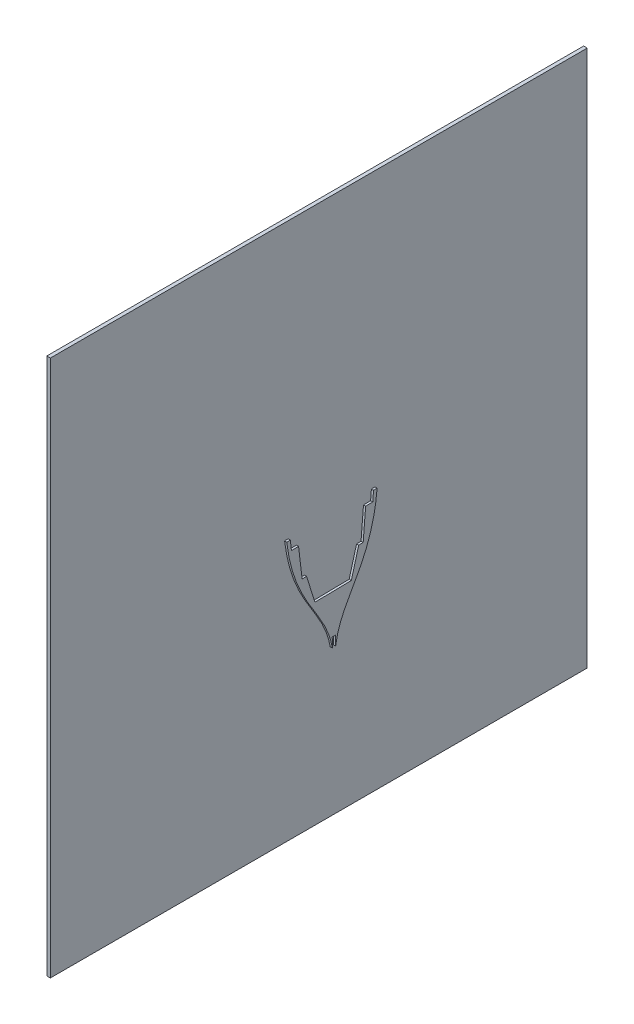
SolidWorks part; units mm, degrees
ref_plane "Plan de face" through (0, 0, 0) normal (0, 0, 1) x (1, 0, 0)
ref_plane "Plan de dessus" through (0, 0, 0) normal (0, 1, 0) x (1, 0, 0)
ref_plane "Plan de droite" through (0, 0, 0) normal (1, 0, 0) x (0, 0, -1)
sketch "Esquisse1" plane through (0, 0, 0) normal (0, 0, 1) x (1, 0, 0)
  point P0 (-20, 0)
  dimension "D1" = 20
sketch3d "Esquisse3D1"
  line L1 (-20, 1121.2893, 777.275) -> (-20, 1121.2893, -722.725)
  line L2 (-20, 1121.2893, 777.275) -> (-20, -378.7107, 777.275)
  line L3 (-20, -378.7107, 777.275) -> (-20, -378.7107, -722.725)
  line L4 (-20, 1121.2893, -722.725) -> (-20, -378.7107, -722.725)
  dimension "D1" = 1500
  dimension "D2" = 1500
extrude "Boss.-Extru.2" add sketch "Esquisse3D1" along direction (1, 0, 0) on the side of the normal blind 10 contours L2 L1 L4 L3
sketch "Esquisse4" plane through (-10, 0, 0) normal (1, 0, 0) x (0, 0, -1)
  line L0 (0, 0) -> (-7.701, 425.1082) construction
  line L1 (169.3944, 339.9131) -> (-188.5193, 333.4294) construction
  line L2 (-187.2006, 249.23) -> (169.0622, 255.6839) construction
  line L3 (-144.268, 175.2448) -> (126.4811, 180.1495) construction
sketch "Esquisse5" plane through (0, 0, 0) normal (1, 0, 0) x (0, 0, -1)
  line L0 (-7.701, 425.1082) -> (0, 0) construction
  line L2 (0, 0) -> (3.7943, 58.3884) construction
  line L3 (3.7943, 58.3884) -> (5.4733, 142.9265) construction
  line L4 (5.4733, 142.9265) -> (102.9324, 168.1895) construction
  line L5 (102.9324, 168.1895) -> (119.6506, 366.1761) construction
  line L8 (119.6506, 366.1761) -> (109.6506, 365.9949)
  line L9 (109.6506, 365.9949) -> (107.5151, 338.7922)
  line L10 (169.3944, 339.9131) -> (-188.5193, 333.4294) construction
  line L11 (107.5151, 338.7922) -> (87.5835, 338.4311)
  line L12 (87.5835, 338.4311) -> (80.739, 254.0839)
  line L13 (-187.2006, 249.23) -> (169.0622, 255.6839) construction
  line L14 (80.739, 254.0839) -> (68.2687, 253.858)
  line L15 (68.2687, 253.858) -> (47.6553, 178.7215)
  line L16 (-144.268, 175.2448) -> (126.4811, 180.1495) construction
  line L17 (47.6553, 178.7215) -> (-54.0971, 176.8782)
  line L18 (0, 0) -> (-5.9065, 58.2127) construction
  line L19 (-5.9065, 58.2127) -> (-10.6464, 142.6345) construction
  line L20 (-10.6464, 142.6345) -> (-108.9565, 164.351) construction
  line L21 (-108.9565, 164.351) -> (-132.8346, 361.6022) construction
  line L22 (-77.4184, 251.2188) -> (-54.0971, 176.8782)
  line L23 (-89.8887, 250.9929) -> (-77.4184, 251.2188)
  line L24 (-99.7836, 335.0369) -> (-89.8887, 250.9929)
  line L25 (-119.7152, 334.6758) -> (-99.7836, 335.0369)
  line L26 (-122.8346, 361.7834) -> (-119.7152, 334.6758)
  line L27 (-132.8346, 361.6022) -> (-122.8346, 361.7834)
  spline S0 degree 4 poles (0, 0) (3.7943, 58.3884) (5.4733, 142.9265) (102.9324, 168.1895) (119.6506, 366.1761) knots 0 0 0 0 0 1 1 1 1 1
  spline S1 degree 4 poles (0, 0) (-5.9065, 58.2127) (-10.6464, 142.6345) (-108.9565, 164.351) (-132.8346, 361.6022) knots 0 0 0 0 0 1 1 1 1 1
  point P30 (-3.2209, 177.7999)
  dimension "D1" = 10
extrude "Boss.-Extru.3" add sketch "Esquisse5" along normal blind 6 separate body
sketch "Esquisse6" plane through (6, 0, 0) normal (1, 0, 0) x (0, 0, -1)
  line L0 (-5.2544, 41.5611) -> (-5.7435, 68.5611)
  line L1 (-5.7435, 68.5611) -> (3.2565, 68.7241)
  line L2 (3.2565, 68.7241) -> (3.7456, 41.7241)
  line L3 (3.7456, 41.7241) -> (117.0633, -47.527)
  line L4 (117.0633, -47.527) -> (-85.2277, -65.22)
  line L5 (-85.2277, -65.22) -> (-5.2544, 41.5611)
  line L6 (-5.2544, 41.5611) -> (3.7456, 41.7241) construction
  line L7 (-144.268, 175.2448) -> (126.4811, 180.1495) construction
  spline S0 degree 4 poles (-132.8346, 361.6022) (-108.9565, 164.351) (-10.6464, 142.6345) (-5.9065, 58.2127) (0, 0) knots 0 0 0 0 0 1 1 1 1 1 construction
  spline S1 degree 4 poles (0, 0) (3.7943, 58.3884) (5.4733, 142.9265) (102.9324, 168.1895) (119.6506, 366.1761) knots 0 0 0 0 0 1 1 1 1 1 construction
  dimension "D1" = 9
  dimension "D2" = 27
extrude "Enlèv. mat.-Extru.1" cut sketch "Esquisse6" against normal blind 6
